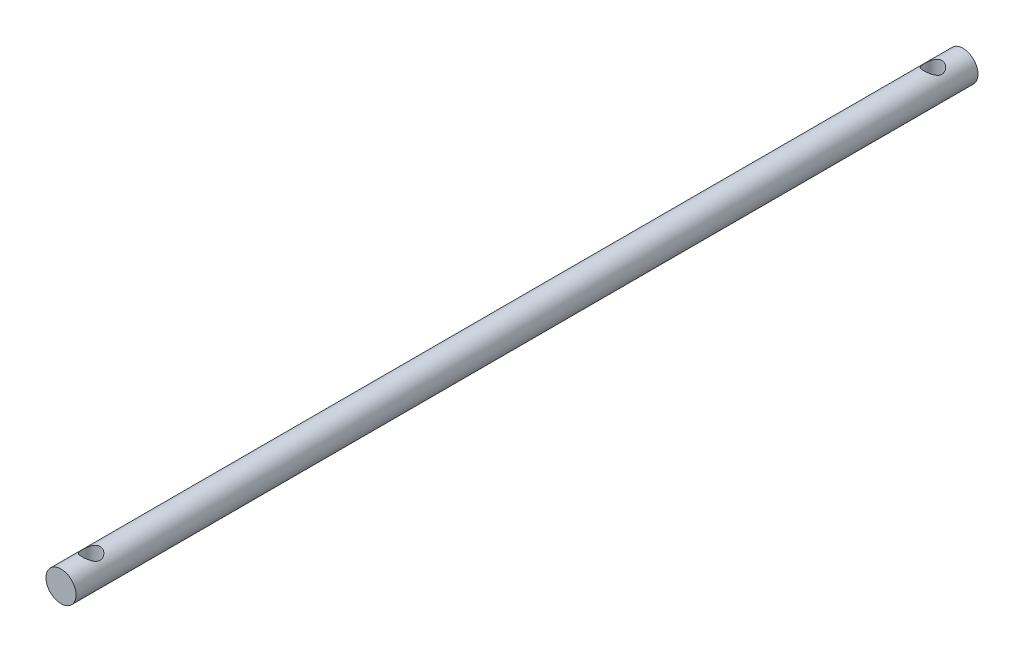
SolidWorks part; units mm, degrees
material "6061 Alloy"
ref_plane "Front Plane" through (0, 0, 0) normal (0, 0, 1) x (1, 0, 0)
ref_plane "Top Plane" through (0, 0, 0) normal (0, 1, 0) x (1, 0, 0)
ref_plane "Right Plane" through (0, 0, 0) normal (1, 0, 0) x (0, 0, -1)
sketch "Sketch1" plane through (0, 0, 0) normal (0, 0, 1) x (1, 0, 0)
  line L0 (55, 0) -> (-55, 0) construction
  circle A0 centre (0, 0) radius 2.5
  dimension "D1" = 5
extrude "Boss-Extrude1" add sketch "Sketch1" along normal blind 150
sketch "Sketch2" plane through (0, 0, 0) normal (0, 1, 0) x (1, 0, 0)
  line L0 (0, -2.75) -> (0, 2.75) construction
  line L1 (-2.5, -150) -> (2.5, -150) construction
  line L2 (2.5, 0) -> (-2.5, 0) construction
  circle A0 centre (0, -5) radius 1.5
  circle A1 centre (0, -145) radius 1.5
  dimension "D1" = 3
  dimension "D2" = 5
  dimension "D3" = 5
extrude "Cut-Extrude1" cut sketch "Sketch2" against normal mid plane 30
